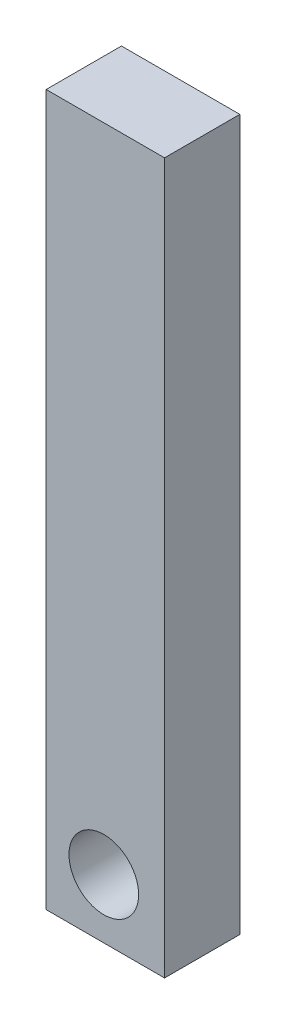
SolidWorks part; units mm, degrees
ref_plane "Front Plane" through (0, 0, 0) normal (0, 0, 1) x (1, 0, 0)
ref_plane "Top Plane" through (0, 0, 0) normal (0, 1, 0) x (1, 0, 0)
ref_plane "Right Plane" through (0, 0, 0) normal (1, 0, 0) x (0, 0, -1)
sketch "Sketch1" plane through (0, 0, 0) normal (0, 0, 1) x (1, 0, 0)
  line L1 (0, 0) -> (5, 0)
  line L2 (0, 0) -> (0, 30)
  line L3 (0, 30) -> (5, 30)
  line L4 (5, 0) -> (5, 30)
  circle A0 centre (2.4351, 2.5) radius 1.47
  dimension "D3" = 2.94
  dimension "D4" = 2.5
  dimension "D1" = 5
  dimension "D2" = 30
extrude "Boss-Extrude1" add sketch "Sketch1" along normal blind 3.18
